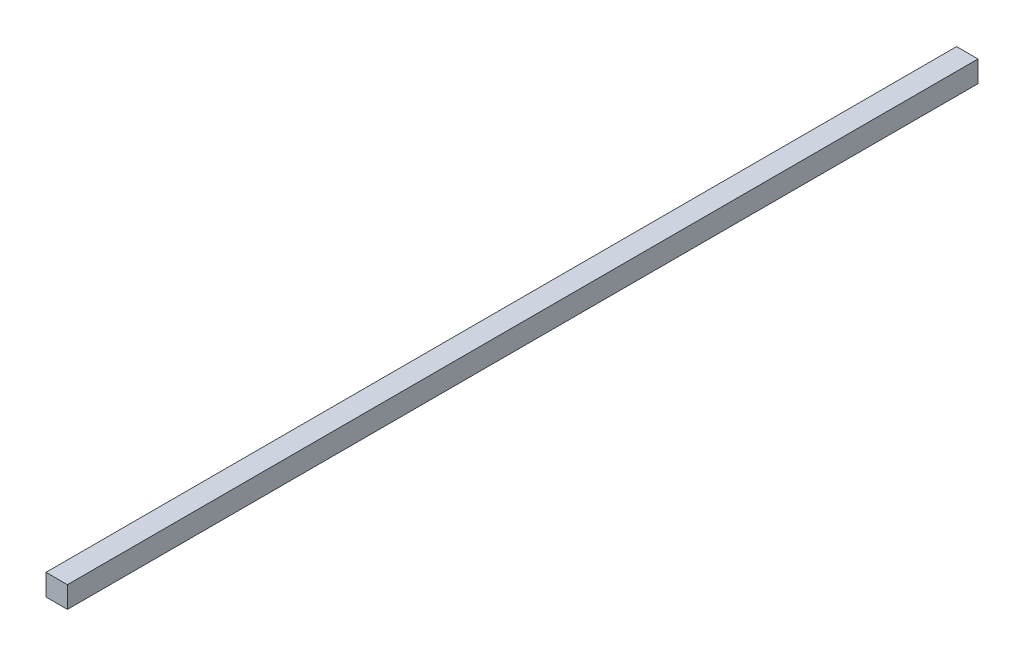
SolidWorks part; units mm, degrees
material "Plain Carbon Steel"
ref_plane "Front Plane" through (0, 0, 0) normal (0, 0, 1) x (1, 0, 0)
ref_plane "Top Plane" through (0, 0, 0) normal (0, 1, 0) x (1, 0, 0)
ref_plane "Right Plane" through (0, 0, 0) normal (1, 0, 0) x (0, 0, -1)
sketch "Sketch1" plane through (0, 0, 0) normal (0, 0, 1) x (1, 0, 0)
  line L0 (-3, 0) -> (3, 0) construction
  line L1 (0, -3) -> (0, 3) construction
  line L5 (-3, 3) -> (3, 3) construction
  line L7 (-3, 3) -> (-3, -3) construction
  line L8 (3, -3) -> (3, 3) construction
  line L13 (-3, -3) -> (3, -3) construction
  point P0 (0, 0)
  point P4 (0, 0)
  point P9 (0, 0)
  point P22 (0, 3)
  dimension "Thickness" = 6
  dimension "D1" = 6
sketch "Sketch2" plane through (0, 0, 0) normal (0, 1, 0) x (0, 0, -1)
  line L0 (127.5, 0) -> (-127.5, 0) construction
  line L2 (-127.5, 3) -> (127.5, 3) construction
  line L3 (-127.5, 3) -> (-127.5, -3) construction
  line L4 (-127.5, -3) -> (127.5, -3) construction
  line L5 (127.5, 3) -> (127.5, -3) construction
  line L6 (-127.5, 3) -> (127.5, -3) construction
  line L7 (-127.5, -3) -> (127.5, 3) construction
  point P4 (0, 0)
  point P7 (0, 0)
  point P12 (-120.6, 3)
  point P13 (120.6, 3)
  dimension "Length" = 255
  dimension "Width" = 6
  dimension "D1" = 6.9
  dimension "D2" = 6.9
sketch "Sketch3" plane through (0, 0, 0) normal (0, 0, 1) x (1, 0, 0)
  line L3 (-3, 3) -> (3, 3)
  line L17 (3, 3) -> (3, -3)
  line L18 (3, -3) -> (-3, -3)
  line L19 (-3, -3) -> (-3, 3)
extrude "Boss-Extrude1" add sketch "Sketch3" along normal mid plane 255
fillet "Fillet1" [suppressed] radius 0.5
equation "\"D1@Boss-Extrude1\" = \"Length@Sketch2\""
equation "\"D1@Sketch1\"=\"Width@Sketch2\""
equation "\"D1@Sketch2\"=\"Width@Sketch2\"*1.15"
equation "\"D2@Sketch2\"=\"D1@Sketch2\""
